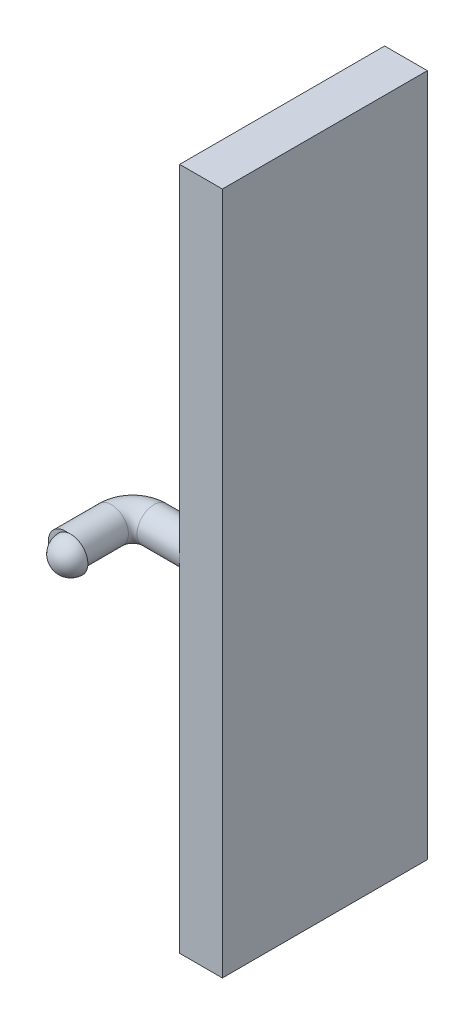
SolidWorks part; units mm, degrees
ref_plane "Front Plane" through (0, 0, 0) normal (1, 0, 0) x (0, 1, 0)
ref_plane "Top Plane" through (0, 0, 0) normal (0, 0, 1) x (0, 1, 0)
ref_plane "Right Plane" through (0, 0, 0) normal (0, 1, 0) x (-1, 0, 0)
sketch "Base" plane through (0, 0, 0) normal (1, 0, 0) x (0, 1, 0)
  line L5 (-50.8, 2.54) -> (50.8, 2.54)
  line L6 (-50.8, 2.54) -> (-50.8, -2.54)
  line L7 (-50.8, -2.54) -> (50.8, -2.54) construction
  line L8 (50.8, 2.54) -> (50.8, -2.54)
  line L9 (-50.8, 2.54) -> (50.8, -2.54) construction
  line L10 (-50.8, -2.54) -> (50.8, 2.54) construction
  line L11 (-50.8, -2.54) -> (50.8, -2.54) construction
  line L12 (-50.8, -2.54) -> (-50.8, -27.94)
  line L13 (-50.8, -27.94) -> (50.8, -27.94)
  line L14 (50.8, -2.54) -> (50.8, -27.94)
  point P0 (0, 0)
  point P1 (0, 0)
  dimension "D1" = 5.08
  dimension "D2" = 25.4
  dimension "D3" = 101.6
ref_plane "Front Pegboard Surface" through (-6.35, 0, 0) normal (1, 0, 0) x (0, 1, 0)
sketch "Peg Base" plane through (-6.35, 0, 0) normal (1, 0, 0) x (0, 1, 0)
  circle A2 centre (0, 0) radius 2.54
  dimension "D1" = 5.08
ref_plane "Back Pegboard Surface" through (-12.7, 0, 0) normal (1, 0, 0) x (0, 1, 0)
ref_plane "Sweep End" through (0, 0, 10) normal (0, 0, 1) x (0, 1, 0)
sketch "Sketch1" plane through (0, 0, 10) normal (0, 0, 1) x (0, 1, 0)
  line L0 (0, 15.08) -> (0, 0) construction
  circle A0 centre (0, 15.08) radius 2.54
  dimension "D1" = 5.08
  dimension "D4" = 15.08
ref_plane "Right Ball Head" through (0, 25.4, 0) normal (0, 1, 0) x (-1, 0, 0)
ref_plane "Plane3" through (0, -25.4, 0) normal (0, 1, 0) x (-1, 0, 0)
extrude "Boss-Extrude1" add sketch "Base" against normal blind 6.35 contours L5 L8 L14 L13 L12 L6
sketch "Sweep" plane through (0, 0, 0) normal (0, 1, 0) x (-1, 0, 0)
  line L0 (6.35, 0) -> (12.7, 0)
  line L1 (12.7, 2.794) -> (12.7, -2.794) construction
  line L2 (6.35, 2.54) -> (6.35, -2.54) construction
  line L3 (0, 0) -> (6.35, 0) construction
  line L4 (15.875, 10) -> (15.875, 3.175)
  line L5 (15.08, 10) -> (0, 10) construction
  arc A0 (12.7, 0) -> (15.875, 3.175) centre (12.7, 3.175) ccw
  dimension "D1" = 6.35
  dimension "D2" = 3.175
  dimension "D3" = 6.825
sketch "Bottom Peg" plane through (-6.35, 0, 0) normal (1, 0, 0) x (0, 1, 0)
  line L0 (0, -25.4) -> (0, 0) construction
  circle A0 centre (0, -25.4) radius 3.175
  dimension "D2" = 6.35
  dimension "D1" = 25.4
sweep "Top Peg" add profiles "Peg Base" path "Sweep"
ref_plane "Plane4" through (-16.35, 0, 0) normal (1, 0, 0) x (0, 1, 0)
extrude "Boss-Extrude2" add sketch "Bottom Peg" against normal up to surface (10 mm away) contours A0 up to plane "Plane4"
sketch "Sketch4" plane through (0, 0, 0) normal (0, 1, 0) x (-1, 0, 0)
  line L0 (17.62, 10) -> (12.54, 10) construction
  line L1 (10.1282, 10) -> (-10.1282, 10) construction
  line L2 (15.08, 12.54) -> (15.08, 10)
  line L3 (15.08, 10) -> (17.62, 10)
  arc A0 (17.62, 10) -> (15.08, 12.54) centre (15.08, 10) ccw
  dimension "D1" = 2.54
revolve "Revolve1" add sketch "Sketch4" angle 360 about L2
sketch "Bottom Ball Head" plane through (0, 0, 0) normal (0, 1, 0) x (-1, 0, 0)
  line L0 (0, 0) -> (0, -25.4)
  line L1 (0, 2.54) -> (0, -27.94) construction
  line L2 (0, -25.4) -> (16.35, -25.4)
  line L3 (16.35, 21.2162) -> (16.35, -21.2162) construction
  line L4 (16.35, -25.4) -> (19.525, -25.4)
  line L5 (16.35, -28.575) -> (16.35, -25.4)
  arc A0 (19.525, -25.4) -> (16.35, -28.575) centre (16.35, -25.4) cw
  dimension "D1" = 25.4
  dimension "D2" = 3.175
revolve "Revolve2" add sketch "Bottom Ball Head" angle 360 about L4
sketch "Sketch6" plane through (0, 0, 0) normal (0, 1, 0) x (-1, 0, 0)
  line L0 (-176.4784, 47.6952) -> (-176.4784, -6.3048)
  line L1 (-176.4784, -6.3048) -> (-117.3049, -6.3048)
  line L2 (-176.4784, 47.6952) -> (-176.4784, 38.8761)
  line L3 (-173.5266, 35.4) -> (-167.2619, 35.4)
  line L4 (-164.3629, 33.495) -> (-165.2879, 10)
  line L5 (55.88, 10) -> (-55.88, 10) construction
  line L6 (-165.2879, 10) -> (-175.5729, 10)
  line L7 (-179.065, 43.151) -> (-173.5266, 43.151)
  arc A0 (-176.4784, 38.8761) -> (-173.5266, 35.4) centre (-172.2325, 39.4902) ccw
  arc A1 (-167.2619, 35.4) -> (-164.3629, 33.495) centre (-167.2619, 32.2417) cw
  dimension "D3" = 4.2901
  dimension "D1" = 54
  dimension "D2" = 25.4
  dimension "D4" = 5.5384
